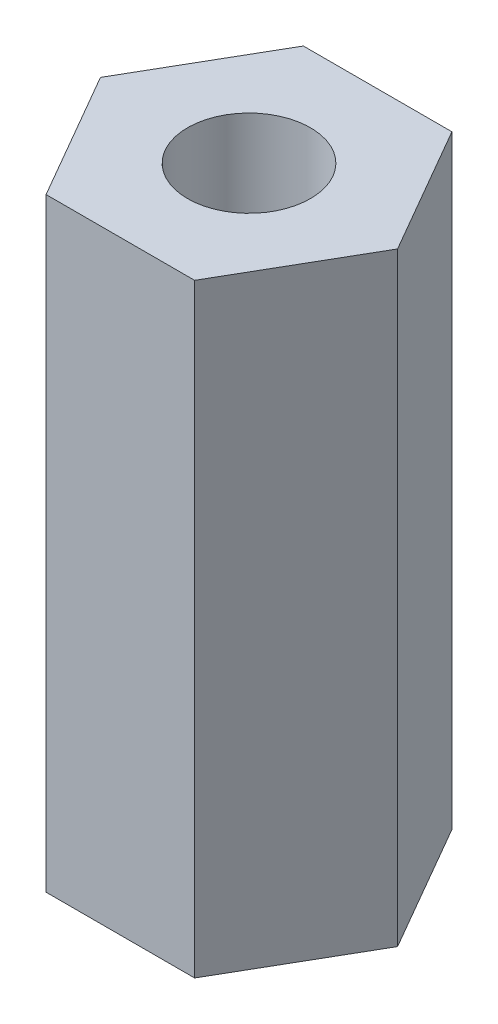
SolidWorks part; units mm, degrees
ref_plane "Front Plane" through (0, 0, 0) normal (0, 0, 1) x (1, 0, 0)
ref_plane "Top Plane" through (0, 0, 0) normal (0, 1, 0) x (1, 0, 0)
ref_plane "Right Plane" through (0, 0, 0) normal (1, 0, 0) x (0, 0, -1)
sketch "Sketch1" plane through (0, 0, 0) normal (0, 1, 0) x (1, 0, 0)
  line L1 (4.5901, 0) -> (2.295, 3.9751)
  line L2 (2.295, 3.9751) -> (-2.295, 3.9751)
  line L3 (-2.295, 3.9751) -> (-4.5901, 0)
  line L4 (-4.5901, 0) -> (-2.295, -3.9751)
  line L5 (-2.295, -3.9751) -> (2.295, -3.9751)
  line L6 (2.295, -3.9751) -> (4.5901, 0)
  circle A1 centre (0, 0) radius 3.9751 construction
  dimension "D2" = 7.9502
extrude "Boss-Extrude1" add sketch "Sketch1" along normal blind 18.669
hole_wizard "Tap Drill for #10 Tap1" positions "Sketch3" profile "Sketch2" hole size "#10-24" standard "Ansi Inch" end condition through all
sketch "Sketch3" plane through (0, 18.669, 0) normal (0, 1, 0) x (-1, 0, 0)
  point P0 (0, 0)
sketch "Sketch2" plane through (0, 18.669, 0) normal (1, 0, 0) x (0, 0, 1)
  line L0 (0, 0) -> (0, 18.669)
  line L1 (0, 18.669) -> (1.8986, 18.669)
  line L2 (1.8986, 18.669) -> (1.8986, 0)
  line L5 (1.8986, 0) -> (0, 0)
  line L11 (0, -6.35) -> (0, 107.95) construction
  dimension "Thru Hole Dia." = 3.7973
  dimension "Thru Hole Depth" = 18.669
